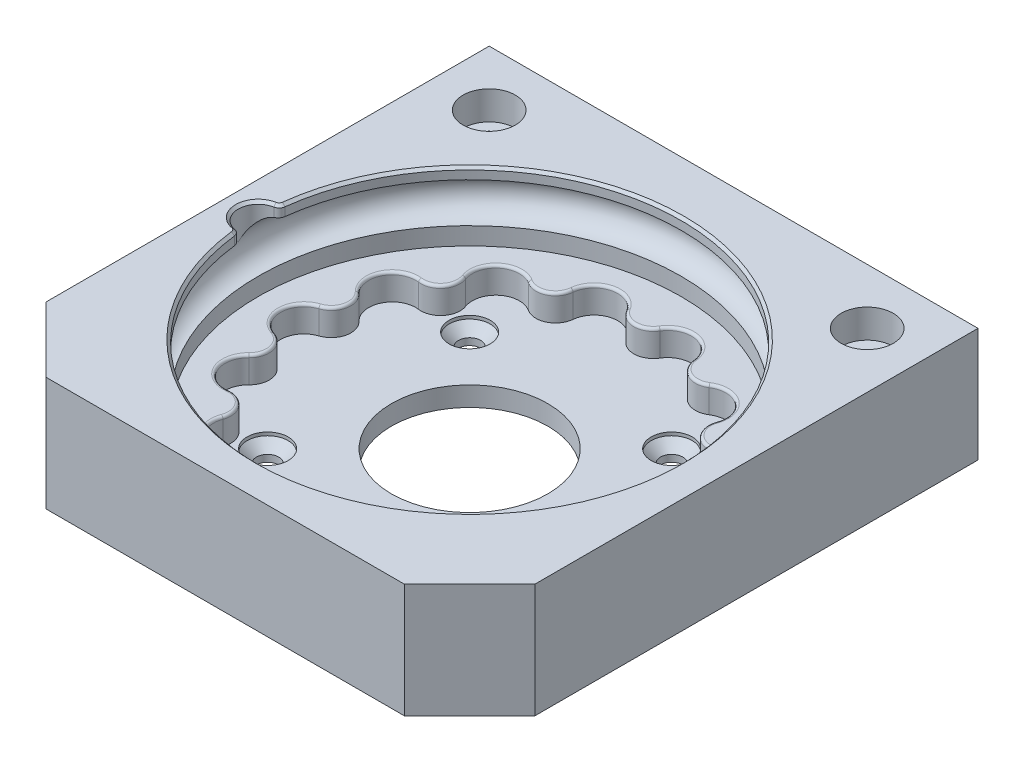
SolidWorks part; units mm, degrees
ref_plane "Front Plane" through (0, 0, 0) normal (0, 0, 1) x (1, 0, 0)
ref_plane "Top Plane" through (0, 0, 0) normal (0, 1, 0) x (1, 0, 0)
ref_plane "Right Plane" through (0, 0, 0) normal (1, 0, 0) x (0, 0, -1)
sketch "Sketch1" plane through (0, 0, 0) normal (0, 1, 0) x (1, 0, 0)
  line L0 (0, 0) -> (7.6226, 33.3969) construction
  line L1 (-37.5, -37.5) -> (37.5, -37.5)
  line L2 (-37.5, -37.5) -> (-37.5, 37.5)
  line L3 (-37.5, 37.5) -> (37.5, 37.5)
  line L4 (37.5, -37.5) -> (37.5, 37.5)
  line L5 (-37.5, -37.5) -> (37.5, 37.5) construction
  line L6 (-37.5, 37.5) -> (37.5, -37.5) construction
  circle A0 centre (0, 0) radius 28.2 construction
  circle A1 centre (0, 28.2) radius 3
  circle A2 centre (12.2355, 25.4073) radius 3
  circle A3 centre (22.0476, 17.5824) radius 3
  circle A4 centre (27.493, 6.2751) radius 3
  circle A5 centre (27.493, -6.2751) radius 3
  circle A6 centre (22.0476, -17.5824) radius 3
  circle A7 centre (12.2355, -25.4073) radius 3
  circle A8 centre (0, -28.2) radius 3
  circle A9 centre (-12.2355, -25.4073) radius 3
  circle A10 centre (-22.0476, -17.5824) radius 3
  circle A11 centre (-27.493, -6.2751) radius 3
  circle A12 centre (-27.493, 6.2751) radius 3
  circle A13 centre (-22.0476, 17.5824) radius 3
  circle A15 centre (-12.2355, 25.4073) radius 3
  arc A16 (2.5633, 26.6413) -> (9.2498, 25.1152) centre (5.652, 24.7632) cw
  arc A17 (13.8687, 22.8908) -> (19.2308, 18.6147) centre (15.8366, 19.8585) cw
  arc A18 (22.4272, 14.6065) -> (25.403, 8.4273) centre (22.8846, 11.0206) cw
  arc A19 (26.5438, 3.4292) -> (26.5438, -3.4292) centre (25.4, 0) cw
  arc A20 (25.403, -8.4273) -> (22.4272, -14.6065) centre (22.8846, -11.0206) cw
  arc A21 (19.2308, -18.6147) -> (13.8687, -22.8908) centre (15.8366, -19.8585) cw
  arc A22 (9.2498, -25.1152) -> (2.5633, -26.6413) centre (5.652, -24.7632) cw
  arc A23 (-2.5633, -26.6413) -> (-9.2498, -25.1152) centre (-5.652, -24.7632) cw
  arc A24 (-13.8687, -22.8908) -> (-19.2308, -18.6147) centre (-15.8366, -19.8585) cw
  arc A25 (-22.4272, -14.6065) -> (-25.403, -8.4273) centre (-22.8846, -11.0206) cw
  arc A26 (-26.5438, -3.4292) -> (-26.5438, 3.4292) centre (-25.4, 0) cw
  arc A27 (-25.403, 8.4273) -> (-22.4272, 14.6065) centre (-22.8846, 11.0206) cw
  arc A28 (-19.2308, 18.6147) -> (-13.8687, 22.8908) centre (-15.8366, 19.8585) cw
  arc A29 (-9.2498, 25.1152) -> (-2.5633, 26.6413) centre (-5.652, 24.7632) cw
  circle A30 centre (0, 0) radius 4.1
  circle A31 centre (0, 0) radius 25.4 construction
  point P0 (0, 0)
  point P46 (6.4564, 28.2875)
  dimension "D1" = 56.4
  dimension "D2" = 6
  dimension "D8" = 8.2
  dimension "D4" = 75
  dimension "D5" = 75
  dimension "D6" = 2.8
  dimension "D3" = 14
  dimension "D7" = 14
sketch "Sketch3" plane through (0, 0, 0) normal (0, 1, 0) x (1, 0, 0)
  line L1 (-37.5, -37.5) -> (37.5, -37.5)
  line L2 (-37.5, -37.5) -> (-37.5, 37.5)
  line L3 (-37.5, 37.5) -> (37.5, 37.5)
  line L4 (37.5, -37.5) -> (37.5, 37.5)
  line L5 (-37.5, -37.5) -> (37.5, 37.5) construction
  line L6 (-37.5, 37.5) -> (37.5, -37.5) construction
  circle A0 centre (0, 0) radius 4.1 construction
  circle A1 centre (0, 0) radius 4.1
  point P0 (0, 0)
extrude "Boss-Extrude1" add sketch "Sketch3" along normal blind 3
sketch "Sketch4" plane through (0, 3, 0) normal (0, 1, 0) x (1, 0, 0)
  line L4 (37.5, -37.5) -> (37.5, 37.5)
  line L5 (37.5, 37.5) -> (-37.5, 37.5)
  line L6 (-37.5, 37.5) -> (-37.5, -37.5)
  line L7 (-37.5, -37.5) -> (37.5, -37.5)
  line L8 (37.5, -37.5) -> (37.5, 37.5)
  line L9 (37.5, 37.5) -> (-37.5, 37.5)
  line L10 (-37.5, 37.5) -> (-37.5, -37.5)
  line L11 (-37.5, -37.5) -> (37.5, -37.5)
  line L12 (-37.5, -37.5) -> (37.5, -37.5)
  line L13 (37.5, -37.5) -> (37.5, 37.5)
  line L14 (37.5, 37.5) -> (-37.5, 37.5)
  line L15 (-37.5, 37.5) -> (-37.5, -37.5)
  line L16 (-37.5, -37.5) -> (37.5, -37.5)
  line L17 (37.5, -37.5) -> (37.5, 37.5)
  line L18 (37.5, 37.5) -> (-37.5, 37.5)
  line L19 (-37.5, 37.5) -> (-37.5, -37.5)
  arc A0 (26.5438, -3.4292) -> (26.5438, 3.4292) centre (25.4, 0) ccw construction
  circle A1 centre (27.493, -6.2751) radius 3
  circle A2 centre (27.493, -6.2751) radius 3
  circle A3 centre (12.2355, 25.4073) radius 3
  circle A4 centre (12.2355, 25.4073) radius 3
  circle A5 centre (0, 28.2) radius 3
  circle A6 centre (0, 28.2) radius 3
  circle A7 centre (-27.493, 6.2751) radius 3
  circle A8 centre (-27.493, 6.2751) radius 3
  circle A9 centre (-27.493, -6.2751) radius 3
  circle A10 centre (-27.493, -6.2751) radius 3
  circle A11 centre (-22.0476, -17.5824) radius 3
  circle A12 centre (-22.0476, -17.5824) radius 3
  circle A13 centre (-12.2355, -25.4073) radius 3
  circle A14 centre (-12.2355, -25.4073) radius 3
  circle A15 centre (0, -28.2) radius 3
  circle A16 centre (0, -28.2) radius 3
  circle A17 centre (12.2355, -25.4073) radius 3
  circle A18 centre (12.2355, -25.4073) radius 3
  circle A19 centre (22.0476, -17.5824) radius 3
  circle A20 centre (22.0476, -17.5824) radius 3
  circle A21 centre (27.493, 6.2751) radius 3
  circle A22 centre (27.493, 6.2751) radius 3
  circle A23 centre (22.0476, 17.5824) radius 3
  circle A24 centre (22.0476, 17.5824) radius 3
  circle A25 centre (0, 0) radius 4.1
  circle A26 centre (0, 0) radius 4.1
  circle A27 centre (-12.2355, 25.4073) radius 3
  circle A28 centre (-12.2355, 25.4073) radius 3
  circle A29 centre (-22.0476, 17.5824) radius 3
  circle A30 centre (-22.0476, 17.5824) radius 3
  arc A31 (25.403, 8.4273) -> (22.4272, 14.6065) centre (22.8846, 11.0206) ccw construction
  arc A32 (19.2308, 18.6147) -> (13.8687, 22.8908) centre (15.8366, 19.8585) ccw construction
  arc A33 (9.2498, 25.1152) -> (2.5633, 26.6413) centre (5.652, 24.7632) ccw construction
  arc A34 (-19.2308, -18.6147) -> (-13.8687, -22.8908) centre (-15.8366, -19.8585) ccw construction
  arc A35 (-9.2498, -25.1152) -> (-2.5633, -26.6413) centre (-5.652, -24.7632) ccw construction
  arc A36 (2.5633, -26.6413) -> (9.2498, -25.1152) centre (5.652, -24.7632) ccw construction
  arc A37 (13.8687, -22.8908) -> (19.2308, -18.6147) centre (15.8366, -19.8585) ccw construction
  arc A38 (22.4272, -14.6065) -> (25.403, -8.4273) centre (22.8846, -11.0206) ccw construction
  arc A39 (-2.5633, 26.6413) -> (-9.2498, 25.1152) centre (-5.652, 24.7632) ccw construction
  arc A40 (-13.8687, 22.8908) -> (-19.2308, 18.6147) centre (-15.8366, 19.8585) ccw construction
  arc A41 (-22.4272, 14.6065) -> (-25.403, 8.4273) centre (-22.8846, 11.0206) ccw construction
  arc A42 (-26.5438, 3.4292) -> (-26.5438, -3.4292) centre (-25.4, 0) ccw construction
  arc A43 (-25.403, -8.4273) -> (-22.4272, -14.6065) centre (-22.8846, -11.0206) ccw construction
  arc A44 (26.5438, -3.4292) -> (26.5438, 3.4292) centre (25.4, 0) ccw
  arc A45 (25.403, 8.4273) -> (22.4272, 14.6065) centre (22.8846, 11.0206) ccw
  arc A46 (19.2308, 18.6147) -> (13.8687, 22.8908) centre (15.8366, 19.8585) ccw
  arc A47 (9.2498, 25.1152) -> (2.5633, 26.6413) centre (5.652, 24.7632) ccw
  arc A48 (-19.2308, -18.6147) -> (-13.8687, -22.8908) centre (-15.8366, -19.8585) ccw
  arc A49 (-9.2498, -25.1152) -> (-2.5633, -26.6413) centre (-5.652, -24.7632) ccw
  arc A50 (2.5633, -26.6413) -> (9.2498, -25.1152) centre (5.652, -24.7632) ccw
  arc A51 (13.8687, -22.8908) -> (19.2308, -18.6147) centre (15.8366, -19.8585) ccw
  arc A52 (22.4272, -14.6065) -> (25.403, -8.4273) centre (22.8846, -11.0206) ccw
  arc A53 (-2.5633, 26.6413) -> (-9.2498, 25.1152) centre (-5.652, 24.7632) ccw
  arc A54 (-13.8687, 22.8908) -> (-19.2308, 18.6147) centre (-15.8366, 19.8585) ccw
  arc A55 (-22.4272, 14.6065) -> (-25.403, 8.4273) centre (-22.8846, 11.0206) ccw
  arc A56 (-26.5438, 3.4292) -> (-26.5438, -3.4292) centre (-25.4, 0) ccw
  arc A57 (-25.403, -8.4273) -> (-22.4272, -14.6065) centre (-22.8846, -11.0206) ccw
  line M24 (37.5, -37.5) -> (37.5, 37.5)
  line M25 (37.5, 37.5) -> (-37.5, 37.5)
  line M26 (-37.5, 37.5) -> (-37.5, -37.5)
  line M27 (-37.5, -37.5) -> (37.5, -37.5)
  dimension "D1" = 0
  dimension "D2" = 0
  dimension "D3" = 0
  dimension "D4" = 0
  dimension "D5" = 0
  dimension "D6" = 0
  dimension "D7" = 0
  dimension "D8" = 0
  dimension "D9" = 0
  dimension "D10" = 0
  dimension "D11" = 0
  dimension "D12" = 0
  dimension "D13" = 0
  dimension "D14" = 0
  dimension "D15" = 0
  dimension "D16" = 0
  dimension "D17" = 0
extrude "Boss-Extrude2" add sketch "Sketch4" along normal blind 4 contours A57 A10 A56 A8 A55 A30 A54 A28 A53 A6 A47 A4 A46 A24 A45 A22 A44 A2 A52 A20 A51 A18 A50 A16 A49 A14 A48 A12 M27 M24 M25 M26 | A24 | A22 | A2 | A20 | A18 | A16 | A14 | A12 | A10 | A8 | A30 | A28 | A6 | A4
sketch "Sketch5" plane through (0, 7, 0) normal (0, 1, 0) x (1, 0, 0)
  line L4 (-37.5, -37.5) -> (37.5, -37.5)
  line L5 (37.5, -37.5) -> (37.5, 37.5)
  line L6 (37.5, 37.5) -> (-37.5, 37.5)
  line L7 (-37.5, 37.5) -> (-37.5, -37.5)
  line L8 (-37.5, -37.5) -> (37.5, -37.5)
  line L9 (37.5, -37.5) -> (37.5, 37.5)
  line L10 (37.5, 37.5) -> (-37.5, 37.5)
  line L11 (-37.5, 37.5) -> (-37.5, -37.5)
  circle A0 centre (0, 0) radius 32.45
  circle A1 centre (-32.45, 0) radius 3.05 construction
  circle A2 centre (0, 0) radius 29.4 construction
  dimension "D2" = 64.9
  dimension "D3" = 6.1
  dimension "D4" = 2
  dimension "D1" = 0
extrude "Boss-Extrude3" add sketch "Sketch5" along normal blind 10.5
sketch "Sketch7" plane through (0, 3, 0) normal (0, 1, 0) x (1, 0, 0)
  line L1 (-12.0018, -12.0018) -> (12.0018, -12.0018) construction
  line L2 (-12.0018, -12.0018) -> (-12.0018, 12.0018) construction
  line L3 (-12.0018, 12.0018) -> (12.0018, 12.0018) construction
  line L4 (12.0018, -12.0018) -> (12.0018, 12.0018) construction
  line L5 (-12.0018, -12.0018) -> (12.0018, 12.0018) construction
  line L6 (-12.0018, 12.0018) -> (12.0018, -12.0018) construction
  point P0 (0, 0)
sketch "Sketch8" plane through (0, 17.5, 0) normal (0, 1, 0) x (1, 0, 0)
  line L0 (37.5, 15.533) -> (15.533, 37.5)
  line L1 (-15.533, 37.5) -> (-37.5, 15.533)
  line L2 (-37.5, 15.533) -> (-37.5, -15.533)
  line L3 (-37.5, -15.533) -> (-15.533, -37.5)
  line L4 (-15.533, -37.5) -> (15.533, -37.5)
  line L5 (15.533, -37.5) -> (37.5, -15.533)
  line L6 (37.5, -15.533) -> (37.5, 15.533)
  line L7 (15.533, 37.5) -> (-15.533, 37.5)
  line L8 (-37.5, 37.5) -> (-37.5, -37.5) construction
  circle A0 centre (0, 0) radius 37.5 construction
extrude "Cut-Extrude1" [suppressed] cut sketch "Sketch8" against normal through all flip side to cut
chamfer "Chamfer1" distance 10 angle 45 2 edges at (37.5, 8.75, 37.5) (-37.5, 8.75, 37.5)
sketch "Sketch11" plane through (0, 0, 0) normal (0, 0, 1) x (1, 0, 0)
  line L0 (-32.45, 17.5) -> (-32.45, 7) construction
  line L1 (32.45, 17.5) -> (-32.45, 17.5) construction
  line L4 (0, 0) -> (0, 37.5091) construction
  circle A0 centre (-32.45, 12.75) radius 3.05
  dimension "D1" = 6.1
  dimension "D2" = 4.75
revolve "Cut-Revolve1" cut sketch "Sketch11" angle 360 about L4
sketch "Sketch12" plane through (0, 17.5, 0) normal (0, 1, 0) x (1, 0, 0)
  line L0 (-32.45, 0) -> (0, 0) construction
  circle A0 centre (-32.45, 0) radius 3.05
  circle A1 centre (0, 0) radius 32.45 construction
  circle A2 centre (0, 0) radius 32.45 construction
  dimension "D1" = 6.1
extrude "Cut-Extrude2" cut sketch "Sketch12" against normal up to surface (1.7034 mm away)
fillet "Fillet2" radius 1 2 edges at (-32.3067, 16.65, -3.0466) (-32.3067, 16.65, 3.0466)
sketch "Sketch14" plane through (0, 0, 0) normal (0, -1, 0) x (1, 0, 0)
  line L1 (-15.5, -15.5) -> (15.5, -15.5) construction
  line L2 (-15.5, -15.5) -> (-15.5, 15.5) construction
  line L3 (-15.5, 15.5) -> (15.5, 15.5) construction
  line L4 (15.5, -15.5) -> (15.5, 15.5) construction
  line L5 (-15.5, -15.5) -> (15.5, 15.5) construction
  line L6 (-15.5, 15.5) -> (15.5, -15.5) construction
  circle A0 centre (0, 0) radius 12
  circle A1 centre (-15.5, 15.5) radius 3.3155 construction
  circle A2 centre (15.5, 15.5) radius 2.5111 construction
  circle A3 centre (15.5, -15.5) radius 2.6783 construction
  circle A4 centre (-15.5, -15.5) radius 2.6959 construction
  dimension "D2" = 24
  dimension "D1" = 31
extrude "Cut-Extrude3" cut sketch "Sketch14" against normal through all
hole_wizard "CSK for M3 Countersunk Flat Head Screw1" positions "Sketch15" profile "Sketch16" countersink size "M3" standard "ISO" end condition through all
sketch "Sketch15" plane through (0, 3, 0) normal (0, 1, 0) x (1, 0, 0)
  point P0 (-15.5, 15.5)
  point P3 (15.5, 15.5)
  point P6 (15.5, -15.5)
  point P9 (-15.5, -15.5)
sketch "Sketch16" plane through (-15.5, 3, -15.5) normal (1, 0, 0) x (0, 0, 1)
  line L0 (0, 0) -> (0, 3)
  line L1 (0, 3) -> (1.7, 3)
  line L2 (1.7, 3) -> (1.7, 1.95)
  line L3 (1.7, 1.95) -> (3.15, 0.5)
  line L4 (3.15, 0.5) -> (3.15, 0)
  line L6 (3.15, 0) -> (0, 0)
  line L7 (-1.7, 1.95) -> (-3.15, 0.5) construction
  line L11 (0, -6.35) -> (0, 107.95) construction
  dimension "Thru Hole Dia." = 3.4
  dimension "Thru Hole Depth" = 3
  dimension "C'Sink Dia." = 6.3
  dimension "C'Sink Angle" = 90
  dimension "Head Clearance" = 0.5
chamfer "Chamfer2" distance 0.4 angle 45 4 edges at (-35.5, 17.5, 0) (-32.4812, 17.5, 3.2957) (-32.4812, 17.5, -3.2957) (32.45, 17.5, 0)
fillet "Fillet3" radius 0.4 28 edges at (-26.1415, 7, 12.5891) (-19.7022, 7, 15.7119) (-18.0905, 7, 22.6848) (-10.9339, 7, 22.7044) (-6.4564, 7, 28.2875) (0, 7, 25.2) (6.4564, 7, 28.2875) (10.9339, 7, 22.7044) (18.0905, 7, 22.6848) (19.7022, 7, 15.7119) (26.1415, 7, 12.5891) (24.5682, 7, 5.6075) (29.0149, 7, 0) (24.5682, 7, -5.6075) (26.1415, 7, -12.5891) (19.7022, 7, -15.7119) (18.0905, 7, -22.6848) (10.9339, 7, -22.7044) (6.4564, 7, -28.2875) (0, 7, -25.2) (-6.4564, 7, -28.2875) (-10.9339, 7, -22.7044) (-18.0905, 7, -22.6848) (-19.7022, 7, -15.7119) (-26.1415, 7, -12.5891) (-24.5682, 7, -5.6075) (-29.0149, 7, 0) (-24.5682, 7, 5.6075)
sketch "Sketch17" plane through (0, 0, -37.5) normal (0, 0, -1) x (-1, 0, 0)
  line L4 (-37.5, 0) -> (37.5, 0)
  line L5 (37.5, 0) -> (37.5, 17.5)
  line L6 (37.5, 17.5) -> (-37.5, 17.5)
  line L7 (-37.5, 17.5) -> (-37.5, 0)
  line L8 (-37.5, 0) -> (37.5, 0)
  line L9 (37.5, 0) -> (37.5, 17.5)
  line L10 (37.5, 17.5) -> (-37.5, 17.5)
  line L11 (-37.5, 17.5) -> (-37.5, 0)
  dimension "D1" = 0
extrude "Boss-Extrude4" add sketch "Sketch17" along normal blind 3
hole_wizard "CBORE for M4 Hex Socket Head Cap Screw1" positions "Sketch18" profile "Sketch19" counterbore size "M4" standard "ISO" end condition through all
sketch "Sketch18" plane through (0, 17.5, 0) normal (0, 1, 0) x (1, 0, 0)
  line L0 (0, 0) -> (0, -6.217) construction
  line L3 (-37.5, 40.5) -> (-37.5, -27.5) construction
  line L4 (-37.5, 40.5) -> (37.5, 40.5) construction
  point P0 (-29, 32)
  point P8 (29, 32)
  dimension "D1" = 58
  dimension "D2" = 8.5
  dimension "D3" = 8.5
sketch "Sketch19" plane through (-29, 17.5, -32) normal (1, 0, 0) x (0, 0, 1)
  line L0 (0, 0) -> (0, 17.5)
  line L1 (0, 17.5) -> (2.25, 17.5)
  line L3 (2.25, 17.5) -> (2.25, 4.4)
  line L4 (2.25, 4.4) -> (4, 4.4)
  line L5 (4, 4.4) -> (4, 0)
  line L7 (4, 0) -> (0, 0)
  line L11 (0, -6.35) -> (0, 107.95) construction
  dimension "Thru Hole Dia." = 4.5
  dimension "Thru Hole Depth" = 17.5
  dimension "C'Bore Dia." = 8
  dimension "C'Bore Depth" = 4.4
equation "\"N\"= 14"
equation "\"Rr\"= 3"
equation "\"R\"= 28.2"
equation "\"E\"= 1.5"
equation "\"D3@Sketch1\"=\"N\""
equation "\"D1@Sketch1\"=\"R\" *2"
equation "\"D2@Sketch1\"=\"Rr\" *2"
